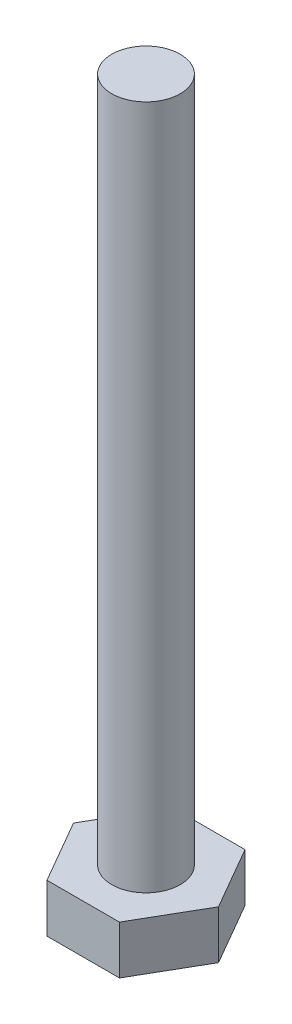
SolidWorks part; units mm, degrees
ref_plane "前视基准面" through (0, 0, 0) normal (0, 0, 1) x (1, 0, 0)
ref_plane "上视基准面" through (0, 0, 0) normal (0, 1, 0) x (1, 0, 0)
ref_plane "右视基准面" through (0, 0, 0) normal (1, 0, 0) x (0, 0, -1)
sketch "草图1" plane through (0, 0, 0) normal (0, 1, 0) x (1, 0, 0)
  circle A0 centre (0, 0) radius 1.5
  dimension "D1" = 3
extrude "凸台-拉伸1" add sketch "草图1" along normal blind 30
sketch "草图3" plane through (0, 0, 0) normal (0, -1, 0) x (1, 0, 0)
  line L1 (3.1754, 0) -> (1.5877, 2.75)
  line L2 (1.5877, 2.75) -> (-1.5877, 2.75)
  line L3 (-1.5877, 2.75) -> (-3.1754, 0)
  line L4 (-3.1754, 0) -> (-1.5877, -2.75)
  line L5 (-1.5877, -2.75) -> (1.5877, -2.75)
  line L6 (1.5877, -2.75) -> (3.1754, 0)
  circle A0 centre (0, 0) radius 2.75 construction
  dimension "D1" = 5.5
extrude "凸台-拉伸2" add sketch "草图3" along normal blind 2.12 contours L5 L6 L1 L2 L3 L4
